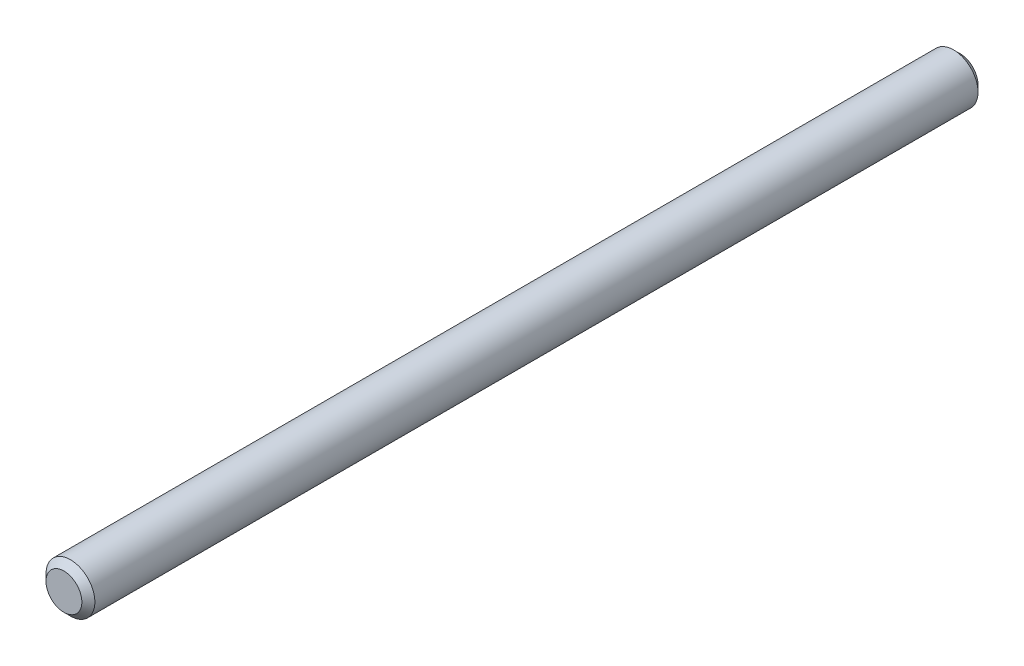
SolidWorks part; units mm, degrees
ref_plane "Ön Düzlem" through (0, 0, 0) normal (0, 0, 1) x (1, 0, 0)
ref_plane "Üst Düzlem" through (0, 0, 0) normal (0, 1, 0) x (1, 0, 0)
ref_plane "Sağ Düzlem" through (0, 0, 0) normal (1, 0, 0) x (0, 0, -1)
sketch "Çizim1" plane through (0, 0, 0) normal (0, 0, 1) x (1, 0, 0)
  circle A0 centre (0, 0) radius 7.5
  dimension "D1" = 15
extrude "Yükseklik-Ekstrüzyon1" add sketch "Çizim1" along normal mid plane 275
chamfer "Pah1" distance 2 angle 45 2 edges at (7.5, 0, -137.5) (7.5, 0, 137.5)
